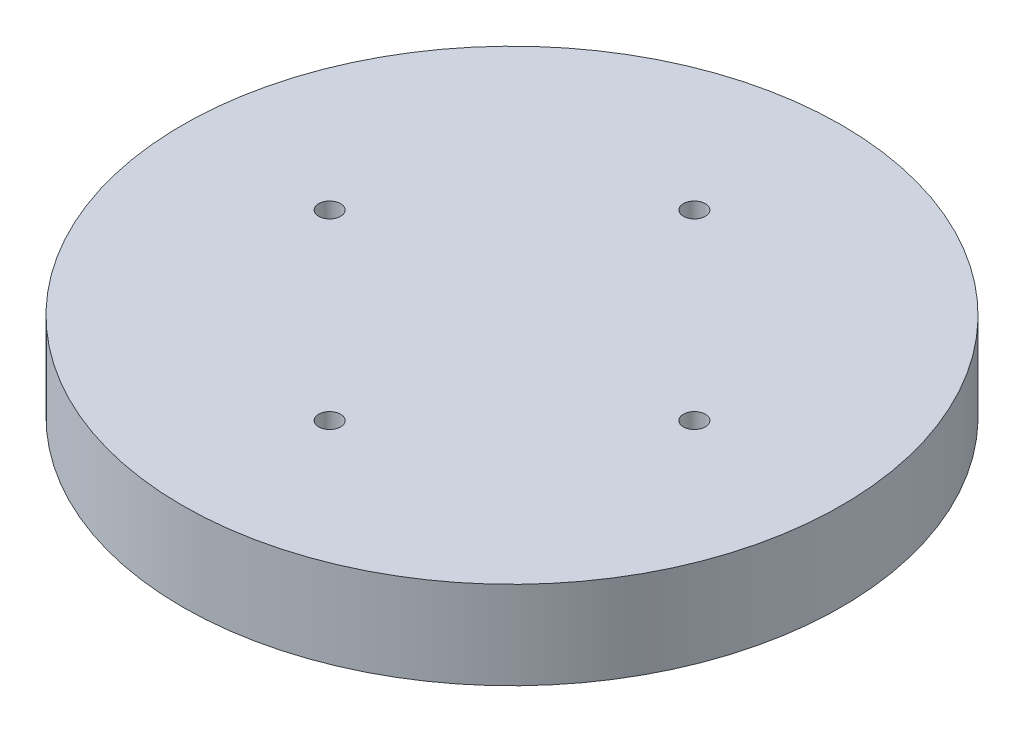
SolidWorks part; units mm, degrees
ref_plane "Front Plane" through (0, 0, 0) normal (0, 0, 1) x (1, 0, 0)
ref_plane "Top Plane" through (0, 0, 0) normal (0, 1, 0) x (1, 0, 0)
ref_plane "Right Plane" through (0, 0, 0) normal (1, 0, 0) x (0, 0, -1)
sketch "Sketch1" plane through (0, 0, 0) normal (0, 1, 0) x (1, 0, 0)
  line L5 (-53.033, 53.033) -> (53.033, -53.033) construction
  line L6 (-53.7618, -53.7618) -> (66.2382, 66.2382) construction
  circle A0 centre (0, 0) radius 75
  point P0 (0, 0)
  dimension "D3" = 150
  dimension "D1" = 120
  dimension "D2" = 120
extrude "Boss-Extrude1" add sketch "Sketch1" along normal blind 20
sketch "Sketch2" plane through (0, 20, 0) normal (0, 1, 0) x (1, 0, 0)
  circle A0 centre (0, 41.5) radius 2.5
  circle A8 centre (41.5, 0) radius 2.5
  circle A9 centre (0, -41.5) radius 2.5
  circle A10 centre (-41.5, 0) radius 2.5
  point P12 (0, 0.25)
  point P13 (0, 0)
  dimension "D1" = 5
  dimension "D2" = 41.5
  dimension "D3" = 4
extrude "Cut-Extrude1" cut sketch "Sketch2" against normal up to next
